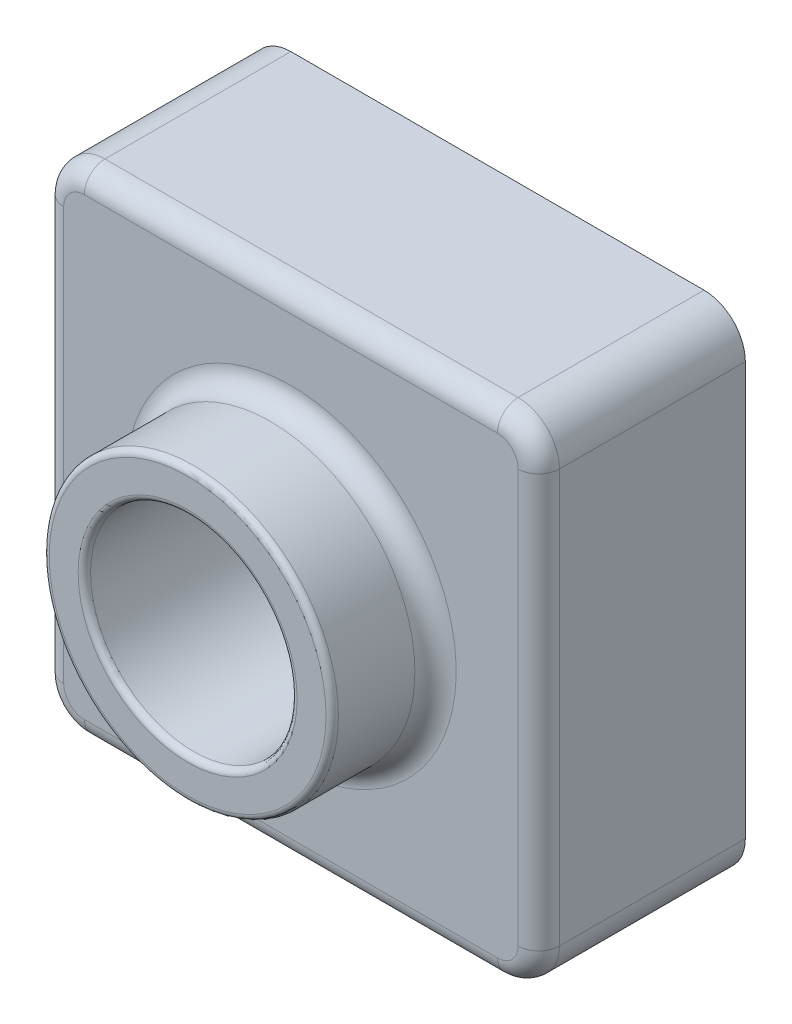
SolidWorks part; units mm, degrees
ref_plane "Front Plane" through (0, 0, 0) normal (0, 0, 1) x (1, 0, 0)
ref_plane "Top Plane" through (0, 0, 0) normal (0, 1, 0) x (1, 0, 0)
ref_plane "Right Plane" through (0, 0, 0) normal (1, 0, 0) x (0, 0, -1)
sketch "Sketch1" plane through (0, 0, 0) normal (0, 0, 1) x (1, 0, 0)
  line L1 (0, 0) -> (120, 0)
  line L2 (0, 0) -> (0, 120)
  line L3 (0, 120) -> (120, 120)
  line L4 (120, 0) -> (120, 120)
  dimension "D1" = 120
extrude "Boss-Extrude1" add sketch "Sketch1" along normal blind 50
sketch "Sketch2" plane through (0, 0, 50) normal (0, 0, 1) x (1, 0, 0)
  line L0 (120, 0) -> (120, 120) construction
  line L1 (0, 0) -> (120, 0) construction
  circle A0 centre (60, 60) radius 35
  dimension "D1" = 70
  dimension "D2" = 60
  dimension "D3" = 60
extrude "Boss-Extrude2" add sketch "Sketch2" along normal blind 25
sketch "Sketch3" plane through (0, 0, 75) normal (0, 0, 1) x (1, 0, 0)
  circle A2 centre (60, 60) radius 25
  circle A3 centre (60, 60) radius 25
  dimension "D1" = 10
extrude "Cut-Extrude1" cut sketch "Sketch3" against normal through all
fillet "Fillet1" radius 10 4 edges at (0, 0, 25) (0, 120, 25) (120, 0, 25) (120, 120, 25)
fillet "Fillet2" radius 1.5 2 edges at (95, 60, 75) (85, 60, 75)
fillet "Fillet3" radius 5 9 edges at (2.9289, 117.0711, 50) (60, 120, 50) (117.0711, 117.0711, 50) (120, 60, 50) (117.0711, 2.9289, 50) (60, 0, 50) (2.9289, 2.9289, 50) (0, 60, 50) (95, 60, 50)
shell "Shell1" thickness 2
